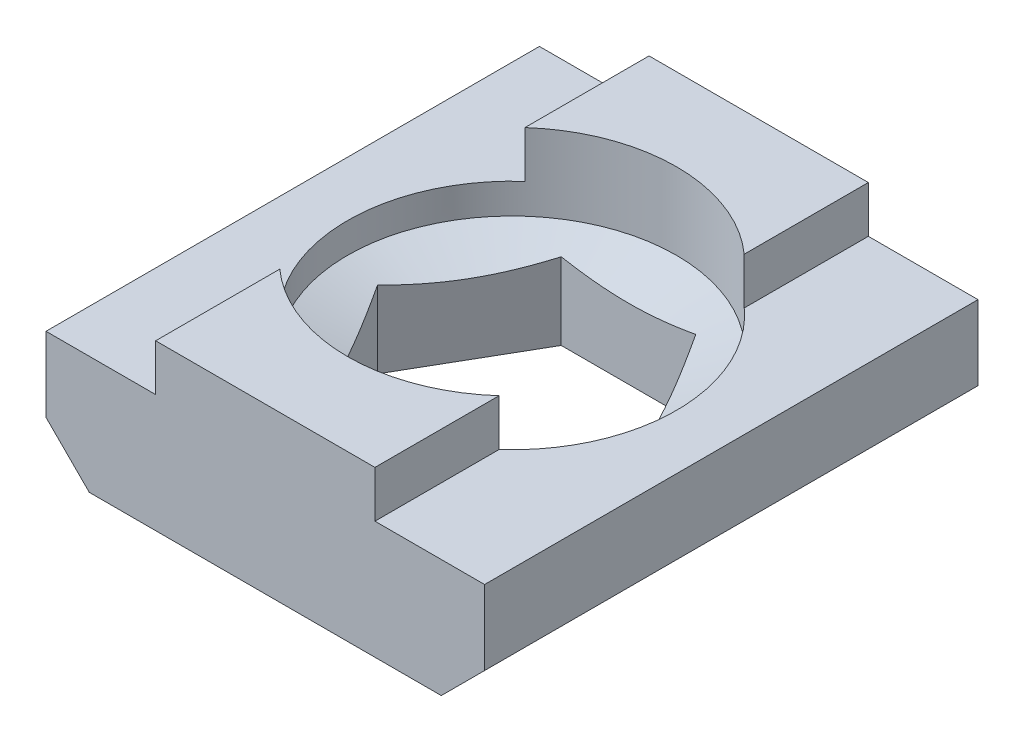
SolidWorks part; units mm, degrees
ref_plane "Front Plane" through (0, 0, 0) normal (0, 0, 1) x (1, 0, 0)
ref_plane "Top Plane" through (0, 0, 0) normal (0, 1, 0) x (1, 0, 0)
ref_plane "Right Plane" through (0, 0, 0) normal (1, 0, 0) x (0, 0, -1)
sketch "Sketch1" plane through (0, 0, 0) normal (1, 0, 0) x (0, 0, -1)
  line L1 (-9, 3) -> (9, 3)
  line L2 (-9, 3) -> (-9, -3)
  line L3 (-9, -3) -> (9, -3)
  line L4 (9, 3) -> (9, -3)
  line L5 (-9, 3) -> (9, -3) construction
  line L6 (-9, -3) -> (9, 3) construction
  point P0 (0, 0)
  dimension "D1" = 18
  dimension "D2" = 6
extrude "Boss-Extrude1" add sketch "Sketch1" along normal mid plane 8
sketch "Sketch4" plane through (0, 0, 9) normal (0, 0, 1) x (1, 0, 0)
  line L0 (-4, 1.3) -> (-4, -3)
  line L1 (-4, -3) -> (-6.42, -3)
  line L2 (-4, 3) -> (-4, -3) construction
  line L3 (-6.42, -3) -> (-8, -1.42)
  line L4 (-4, 1.3) -> (-8, 1.3)
  line L5 (0, 0) -> (0, -6.6802) construction
  line L6 (8, -1.42) -> (8, 1.3)
  line L7 (4, 1.3) -> (8, 1.3)
  line L8 (6.42, -3) -> (8, -1.42)
  line L9 (-8, -1.42) -> (-8, 1.3)
  line L10 (4, -3) -> (6.42, -3)
  line L11 (4, 1.3) -> (4, -3)
  dimension "D1" = 1.3
  dimension "D2" = 8
  dimension "D3" = 45
  dimension "D4" = 2.42
extrude "Boss-Extrude2" add sketch "Sketch4" against normal up to vertex (18 mm away) up to point (-4, 3, -9)
sketch "Sketch2" plane through (0, 3, 0) normal (0, 1, 0) x (1, 0, 0)
  circle A0 centre (0, 0) radius 6
  dimension "D1" = 12
extrude "Cut-Extrude1" cut sketch "Sketch2" against normal blind 2
sketch "Sketch5" plane through (0, -3, 0) normal (0, -1, 0) x (1, 0, 0)
  line L1 (-2.4537, 4.25) -> (-4.9075, 0)
  line L2 (-4.9075, 0) -> (-2.4537, -4.25)
  line L3 (-2.4537, -4.25) -> (2.4537, -4.25)
  line L4 (2.4537, -4.25) -> (4.9075, 0)
  line L5 (4.9075, 0) -> (2.4537, 4.25)
  line L6 (2.4537, 4.25) -> (-2.4537, 4.25)
  circle A0 centre (0, 0) radius 4.25 construction
  dimension "D1" = 8.5
extrude "Cut-Extrude2" cut sketch "Sketch5" against normal through all
sketch "Sketch6" plane through (0, 0, 0) normal (1, 0, 0) x (0, 0, -1)
  line L0 (6, 0.2) -> (3.6683, -0.6487)
  line L1 (6, 0.2) -> (6, 1)
  line L2 (6, 1) -> (3.6683, 1)
  line L3 (0, 1) -> (4.25, 1) construction
  line L4 (3.6683, 1) -> (3.6683, -0.6487)
  line L5 (0, 0) -> (0, 4.0174) construction
  dimension "D1" = 6
  dimension "D2" = 70
  dimension "D3" = 0.8
revolve "Cut-Revolve1" cut sketch "Sketch6" angle 360 about L5
